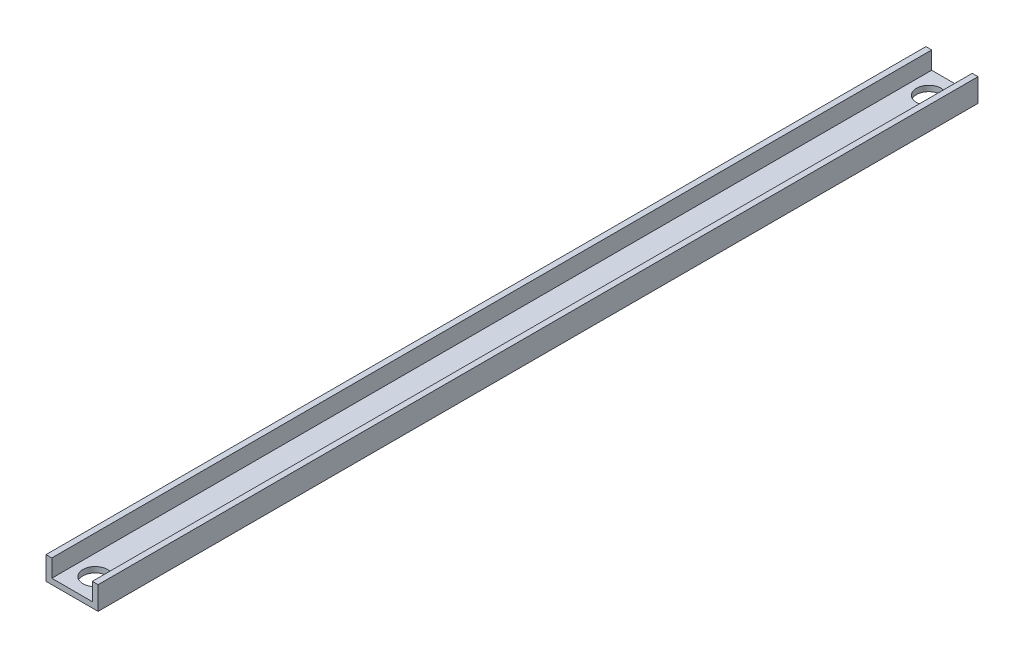
SolidWorks part; units mm, degrees
ref_plane "Front" through (0, 0, 0) normal (0, 0, 1) x (1, 0, 0)
ref_plane "Top" through (0, 0, 0) normal (0, 1, 0) x (1, 0, 0)
ref_plane "Right" through (0, 0, 0) normal (1, 0, 0) x (0, 0, -1)
sketch "Sketch1" plane through (0, 0, 0) normal (0, 0, 1) x (1, 0, 0)
  line L0 (0, -3.175) -> (0, 3.175) construction
  line L1 (-7.1438, 0) -> (7.1438, 0) construction
  line L2 (5.5563, 3.175) -> (-5.5563, 3.175) construction
  line L3 (-7.1437, -3.175) -> (7.1438, -3.175)
  line L4 (-7.1437, -3.175) -> (-7.1438, 3.175)
  line L5 (-7.1438, 3.175) -> (7.1438, 3.175)
  line L6 (7.1438, -3.175) -> (7.1438, 3.175)
  line L7 (-7.1437, -3.175) -> (7.1438, 3.175) construction
  line L8 (-7.1438, 3.175) -> (7.1438, -3.175) construction
  point P3 (0, 0)
  point P4 (0, 0)
  point P8 (0, 0)
  point P13 (7.1438, -1.651)
  point P17 (0, 3.175)
  dimension "Outside Width" = 14.2875
  dimension "Outside Height" = 6.35
  dimension "Wall Thickness" = 1.5875
  dimension "Inside Height" = 4.826
sketch "Sketch2" plane through (0, 0, 0) normal (0, 0, 1) x (1, 0, 0)
  line L0 (-7.1438, 3.175) -> (-7.1438, -3.175)
  line L1 (-7.1438, -3.175) -> (7.1438, -3.175)
  line L2 (7.1438, -3.175) -> (7.1438, 3.175)
  line L3 (-7.1438, 3.175) -> (-5.5563, 3.175)
  line L4 (-5.5563, 3.175) -> (-5.5563, -1.651)
  line L5 (-5.5563, -1.651) -> (5.5563, -1.651)
  line L6 (5.5563, -1.651) -> (5.5563, 3.175)
  line L7 (5.5563, 3.175) -> (7.1438, 3.175)
  point P2 (0, -3.175)
extrude "Boss-Extrude1" add sketch "Sketch2" along normal mid plane 241.3
sketch "Profile" plane through (0, 0, 0) normal (0, 0, 1) x (1, 0, 0)
  line L0 (-7.1438, 0) -> (7.1438, 0) construction
  line L1 (7.1438, 0) -> (7.1438, 3.175) construction
  line L2 (7.1438, 3.175) -> (5.5563, 3.175) construction
  line L3 (7.1438, -3.175) -> (7.1438, 3.175) construction
  line L4 (5.5563, 3.175) -> (5.5563, -1.651) construction
  line L5 (7.1438, 3.175) -> (5.5563, 3.175) construction
  point P14 (0, 0)
  dimension "Width" = 14.2875
  dimension "Height" = 3.175
  dimension "Thickness" = 1.5875
sketch "Length" plane through (0, 0, 0) normal (1, 0, 0) x (0, 0, -1)
  line L0 (-120.65, -3.175) -> (120.65, -3.175) construction
  line L1 (120.65, -3.175) -> (120.65, 3.175) construction
  line L2 (-120.65, -3.175) -> (-120.65, 3.175) construction
  line L3 (-120.65, -3.175) -> (120.65, -3.175) construction
  dimension "Length" = 241.3
sketch "Break Positions" plane through (0, 0, 0) normal (1, 0, 0) x (0, 0, -1)
  line L3 (-120.65, -3.175) -> (-120.65, 3.175) construction
  line L4 (-120.65, -3.175) -> (120.65, -3.175) construction
  line L5 (120.65, 3.175) -> (120.65, -3.175) construction
  line L6 (-120.65, -3.175) -> (120.65, -3.175) construction
  point P0 (-91.4898, -3.175)
  point P1 (91.4898, -3.175)
  dimension "D1" = 29.1602
  dimension "D2" = 29.1602
sketch "Sketch3" plane through (0, -1.651, 0) normal (0, 1, 0) x (1, 0, 0)
  line L0 (5.5563, -120.65) -> (-5.5563, -120.65) construction
  line L1 (5.5563, 120.65) -> (-5.5563, 120.65) construction
  point P0 (0, 114.3)
  point P1 (0, -114.3)
  point P2 (0, 0)
  point P5 (0, 0)
  point P6 (0, -120.65)
  dimension "D1" = 6.35
  dimension "D2" = 6.35
hole_wizard "1/4 Clearance Hole1" positions "Sketch4" profile "Sketch5" hole size "1/4" standard "ANSI Inch" end condition up to next
sketch "Sketch4" plane through (0, -1.651, 0) normal (0, 1, 0) x (-1, 0, 0)
  point P0 (0, -114.3)
  point P3 (0, 114.3)
sketch "Sketch5" plane through (0, -1.651, -114.3) normal (1, 0, 0) x (0, 0, 1)
  line L0 (0, 0) -> (0, 1.524)
  line L1 (0, 1.524) -> (3.3782, 1.524)
  line L2 (3.3782, 1.524) -> (3.3782, 0)
  line L5 (3.3782, 0) -> (0, 0)
  line L11 (0, -6.35) -> (0, 107.95) construction
  dimension "Thru Hole Dia." = 6.7564
  dimension "Thru Hole Depth" = 1.524
